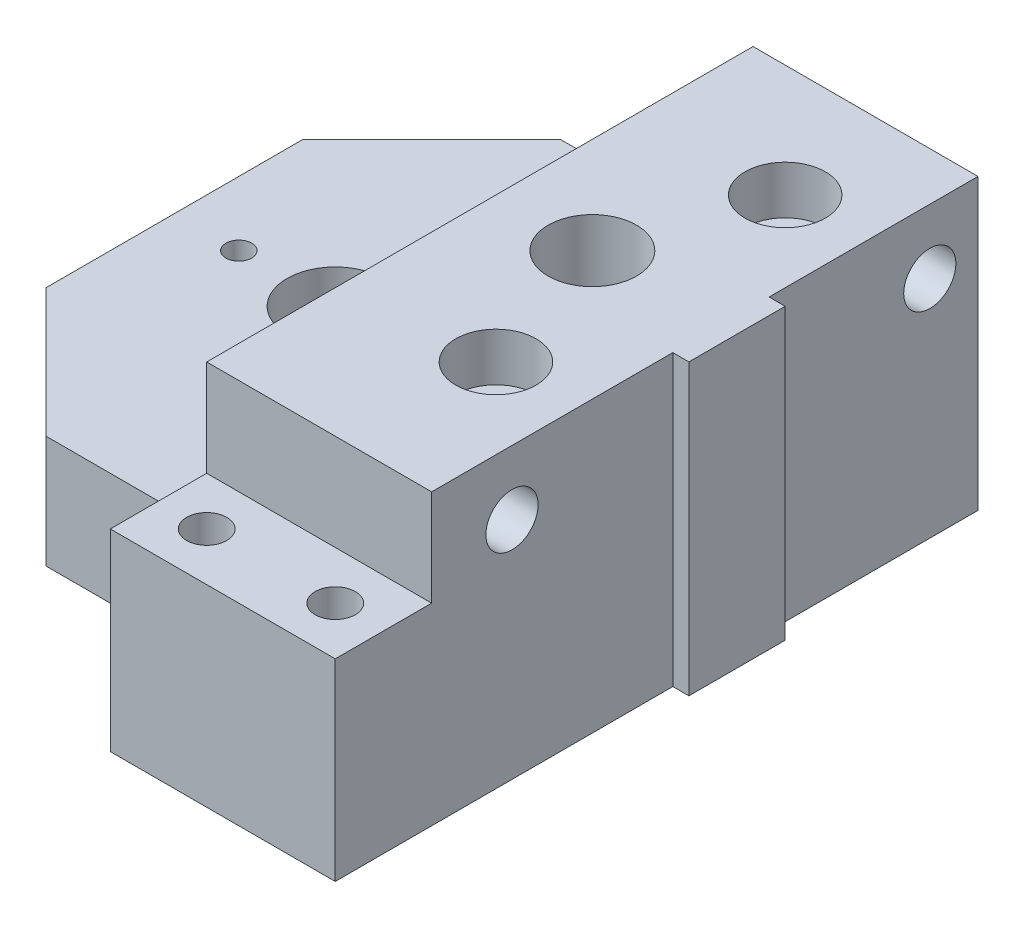
SolidWorks part; units mm, degrees
ref_plane "Front Plane" through (0, 0, 0) normal (0, 0, 1) x (1, 0, 0)
ref_plane "Top Plane" through (0, 0, 0) normal (0, 1, 0) x (1, 0, 0)
ref_plane "Right Plane" through (0, 0, 0) normal (1, 0, 0) x (0, 0, -1)
sketch "Sketch1" plane through (0, 0, 0) normal (0, 1, 0) x (1, 0, 0)
  line L0 (-31.75, -25.4) -> (-6.35, -50.8)
  line L1 (-6.35, -50.8) -> (31.75, -50.8)
  line L2 (31.75, -50.8) -> (31.75, 50.8)
  line L3 (31.75, 50.8) -> (-6.35, 50.8)
  line L4 (-6.35, 50.8) -> (-31.75, 25.4)
  line L5 (-31.75, 25.4) -> (-31.75, -25.4)
  point P6 (0, 0)
  dimension "D1" = 38.1
  dimension "D2" = 63.5
  dimension "D3" = 25.4
  dimension "D4" = 76.2
  dimension "D5" = 101.6
  dimension "D6" = 31.75
  dimension "D7" = 50.8
extrude "Boss-Extrude1" add sketch "Sketch1" along normal mid plane 22.225
sketch "Sketch2" plane through (0, 0, 0) normal (0, 1, 0) x (1, 0, 0)
  line L1 (31.75, -76.2) -> (76.2, -76.2)
  line L2 (31.75, -76.2) -> (31.75, 50.8)
  line L3 (31.75, 50.8) -> (76.2, 50.8)
  line L4 (76.2, -76.2) -> (76.2, 50.8)
  point P8 (0, 0)
  dimension "D1" = 44.45
  dimension "D2" = 127
  dimension "D3" = 76.2
  dimension "D4" = 50.8
extrude "Boss-Extrude2" add sketch "Sketch2" along normal blind 38.1 from offset 11.1125
sketch "Sketch3" plane through (0, 0, 0) normal (0, 1, 0) x (1, 0, 0)
  line L1 (31.75, -57.15) -> (76.2, -57.15)
  line L2 (31.75, -57.15) -> (31.75, 50.8)
  line L3 (31.75, 50.8) -> (76.2, 50.8)
  line L4 (76.2, -57.15) -> (76.2, 50.8)
  point P10 (0, 0)
  dimension "D1" = 44.45
  dimension "D2" = 107.95
  dimension "D3" = 76.2
  dimension "D4" = 50.8
extrude "Boss-Extrude3" add sketch "Sketch3" along normal blind 19.05 from offset 26.9875
sketch "Sketch4" plane through (0, 0, 0) normal (0, 1, 0) x (1, 0, 0)
  line L1 (76.2, -9.4996) -> (79.375, -9.4996)
  line L2 (76.2, -9.4996) -> (76.2, 9.525)
  line L3 (76.2, 9.525) -> (79.375, 9.525)
  line L4 (79.375, -9.4996) -> (79.375, 9.525)
  point P8 (0, 0)
  dimension "D1" = 3.175
  dimension "D2" = 19.0246
  dimension "D3" = 79.375
  dimension "D4" = 9.525
extrude "Boss-Extrude4" add sketch "Sketch4" along normal blind 57.15 from offset 11.1125
sketch "Sketch5" plane through (0, 0, 0) normal (0, 1, 0) x (1, 0, 0)
  circle A0 centre (0, 0) radius 9.525
  point P2 (0, 0)
  dimension "D1" = 19.05
extrude "Cut-Extrude2" cut sketch "Sketch5" against normal through all from offset 11.1125
sketch "Sketch6" plane through (0, 0, 0) normal (0, 1, 0) x (1, 0, 0)
  circle A0 centre (-19.05, 0) radius 2.5527
  circle A1 centre (9.525, -16.51) radius 2.5527
  point P4 (0, 0)
  dimension "D1" = 5.1054
  dimension "D2" = 5.1054
  dimension "D3" = 28.575
  dimension "D4" = 16.51
  dimension "D5" = 19.05
extrude "Cut-Extrude4" cut sketch "Sketch6" against normal blind 12.7 from offset 11.1125
sketch "Sketch7" plane through (0, 0, 0) normal (0, 1, 0) x (1, 0, 0)
  circle A0 centre (9.525, 16.51) radius 2.5527
  point P2 (0, 0)
  dimension "D1" = 5.1054
  dimension "D2" = 9.525
  dimension "D3" = 16.51
extrude "Cut-Extrude6" cut sketch "Sketch7" against normal blind 12.7 from offset 11.1125
sketch "Sketch8" plane through (0, 0, 0) normal (0, 1, 0) x (1, 0, 0)
  circle A0 centre (50.8, 0) radius 8.7312
  point P2 (0, 0)
  dimension "D1" = 17.4625
  dimension "D2" = 50.8
extrude "Cut-Extrude8" cut sketch "Sketch8" against normal blind 31.75 from offset 46.0375
sketch "Sketch9" plane through (0, 0, 0) normal (0, 1, 0) x (1, 0, 0)
  circle A0 centre (41.275, -66.675) radius 3.9688
  circle A1 centre (66.675, -66.675) radius 3.9688
  point P4 (0, 0)
  dimension "D1" = 7.9375
  dimension "D2" = 7.9375
  dimension "D3" = 25.4
  dimension "D4" = 41.275
  dimension "D5" = 66.675
extrude "Cut-Extrude10" cut sketch "Sketch9" against normal blind 19.05 from offset 26.9875
sketch "Sketch10" plane through (0, 0, 0) normal (0, 1, 0) x (1, 0, 0)
  circle A0 centre (60.325, -28.575) radius 5.1562
  circle A1 centre (60.325, 28.575) radius 5.1562
  point P4 (0, 0)
  dimension "D1" = 10.3124
  dimension "D2" = 10.3124
  dimension "D3" = 57.15
  dimension "D4" = 60.325
  dimension "D5" = 28.575
extrude "Cut-Extrude12" cut sketch "Sketch10" against normal through all from offset 46.0375
sketch "Sketch11" plane through (0, 0, 0) normal (0, 1, 0) x (1, 0, 0)
  circle A0 centre (60.325, -28.575) radius 7.9375
  circle A1 centre (60.325, 28.575) radius 7.9375
  point P4 (0, 0)
  dimension "D1" = 15.875
  dimension "D2" = 15.875
  dimension "D3" = 57.15
  dimension "D4" = 60.325
  dimension "D5" = 28.575
extrude "Cut-Extrude14" cut sketch "Sketch11" against normal blind 9.525 from offset 46.0375
sketch "Sketch12" plane through (0, 0, 0) normal (1, 0, 0) x (0, 0, -1)
  circle A0 centre (-41.275, 33.3375) radius 5.1562
  circle A1 centre (41.275, 33.3375) radius 5.1562
  point P4 (0, 0)
  dimension "D1" = 10.3124
  dimension "D2" = 10.3124
  dimension "D3" = 82.55
  dimension "D4" = 41.275
  dimension "D5" = 33.3375
extrude "Cut-Extrude16" cut sketch "Sketch12" along normal through all from offset 31.75
sketch "Sketch13" plane through (0, 0, 0) normal (1, 0, 0) x (0, 0, -1)
  circle A0 centre (-41.275, 33.3375) radius 7.9375
  circle A1 centre (41.275, 33.3375) radius 7.9375
  point P4 (0, 0)
  dimension "D1" = 15.875
  dimension "D2" = 15.875
  dimension "D3" = 82.55
  dimension "D4" = 41.275
  dimension "D5" = 33.3375
extrude "Cut-Extrude18" cut sketch "Sketch13" along normal blind 9.525 from offset 31.75
